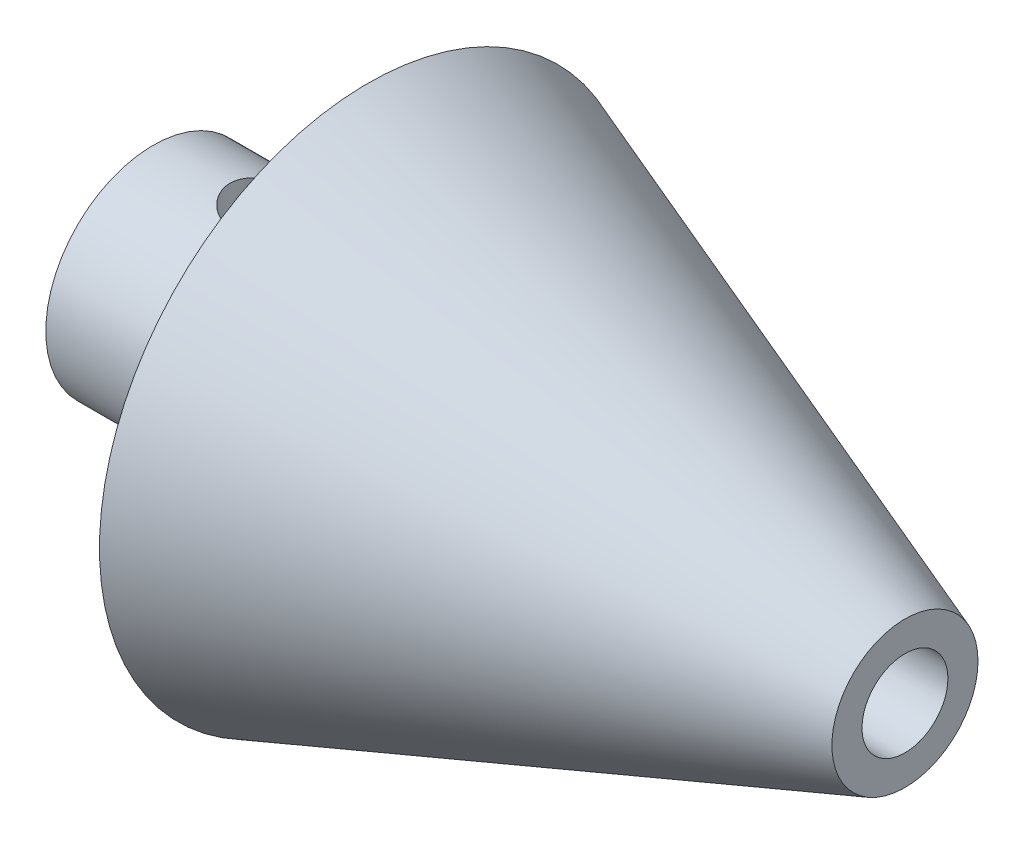
SolidWorks part; units mm, degrees
ref_plane "Alzado" through (0, 0, 0) normal (0, 0, 1) x (1, 0, 0)
ref_plane "Planta" through (0, 0, 0) normal (0, 1, 0) x (1, 0, 0)
ref_plane "Vista lateral" through (0, 0, 0) normal (1, 0, 0) x (0, 0, -1)
sketch "Croquis1" plane through (0, 0, 0) normal (1, 0, 0) x (0, 0, -1)
  line L0 (0, 10) -> (0, -10) construction
  line L1 (-10, 0) -> (10, 0) construction
  circle A0 centre (0, 0) radius 10
  dimension "D1" = 20
extrude "Saliente-Extruir1" add sketch "Croquis1" along normal blind 20
sketch "Croquis2" plane through (20, 0, 0) normal (1, 0, 0) x (0, 0, -1)
  circle A0 centre (0, 0) radius 25
  dimension "D1" = 50
extrude "Saliente-Extruir2" add sketch "Croquis2" along normal blind 50 draft 20
sketch "Croquis3" plane through (70, 0, 0) normal (1, 0, 0) x (0, 0, -1)
  circle A0 centre (0, 0) radius 4
  dimension "D1" = 8
extrude "Cortar-Extruir2" cut sketch "Croquis3" against normal blind 70
hole_wizard "Taladro de margen para 1/41" positions "Croquis3D1" profile "Croquis4" hole size "1/4" standard "Ansi Inch"
sketch3d "Croquis3D1"
  point P0 (10, 9.9749, -0.7076)
  dimension "D1" = 10
sketch "Croquis4" plane through (10, 9.9749, -0.7076) normal (1, 0, 0) x (0, 0.0708, 0.9975)
  line L0 (0, 0) -> (0, 6)
  line L1 (0, 6) -> (3.3782, 6)
  line L2 (3.3782, 6) -> (3.3782, 0)
  line L5 (3.3782, 0) -> (0, 0)
  line L11 (0, -6.35) -> (0, 107.95) construction
  dimension "Diámetro de taladro hasta el siguiente" = 6.7564
  dimension "Profundidad de taladro hasta el siguiente" = 6
